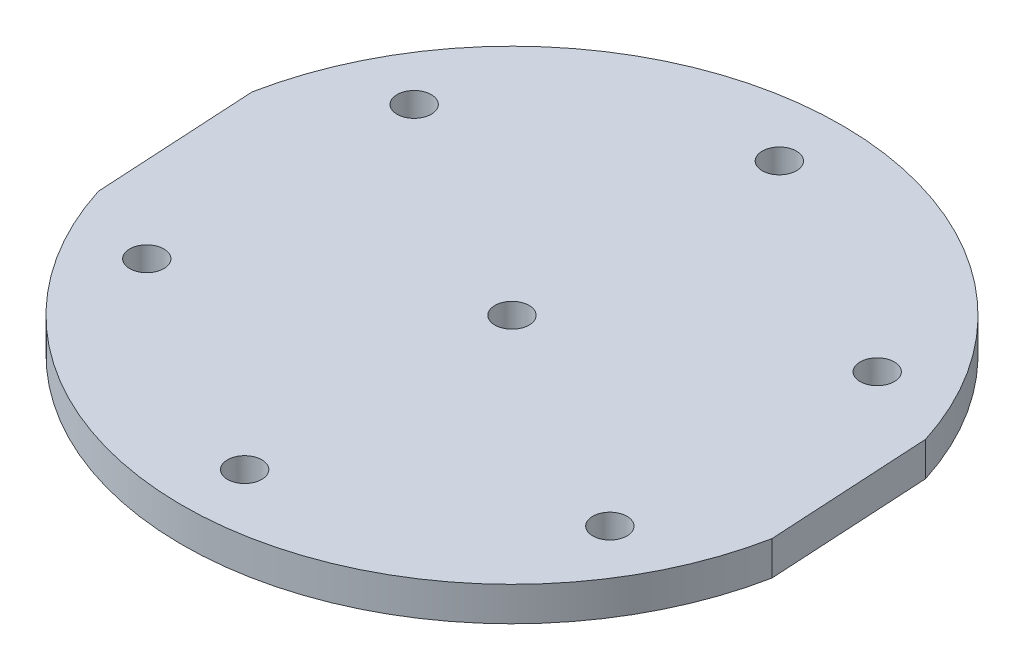
SolidWorks part; units mm, degrees
ref_plane "Спереди" through (0, 0, 0) normal (0, 0, 1) x (1, 0, 0)
ref_plane "Сверху" through (0, 0, 0) normal (0, 1, 0) x (1, 0, 0)
ref_plane "Справа" through (0, 0, 0) normal (1, 0, 0) x (0, 0, -1)
sketch "Эскиз1" plane through (0, 0, 0) normal (0, 1, 0) x (1, 0, 0)
  line L0 (0, 0) -> (-2.7117, 48.1237) construction
  line L1 (45.9548, 14.5395) -> (47.2973, -9.2848)
  line L2 (-47.2973, 9.2848) -> (-45.9548, -14.5395)
  arc A0 (-45.9548, -14.5395) -> (47.2973, -9.2848) centre (0, 0) ccw
  arc A1 (45.9548, 14.5395) -> (-47.2973, 9.2848) centre (0, 0) ccw
  circle A2 centre (0, 0) radius 2.5
  dimension "D1" = 96.4
  dimension "D3" = 5
  dimension "D2" = 46.7
extrude "Бобышка-Вытянуть1" add sketch "Эскиз1" along normal blind 5 contours A0 L1 A1 L2
sketch "Эскиз2" plane through (0, 5, 0) normal (0, 1, 0) x (1, 0, 0)
  line L0 (0, 0) -> (0, 48.2) construction
  arc A0 (45.9548, 14.5395) -> (-47.2973, 9.2848) centre (0, 0) ccw construction
  circle A1 centre (0, 0) radius 2.5 construction
  circle A2 centre (0, 39.1) radius 2.5
  point P7 (0, 39.1)
  point P10 (0, 2.5)
  dimension "D2" = 5
  dimension "D1" = 9.1
extrude "Вырез-Вытянуть1" cut sketch "Эскиз2" against normal blind 20 contours A2
pattern_circular "Круговой массив1" count 6 over 360 about axis through (0, 0, 0) along (0, 1, 0) of "Вырез-Вытянуть1"
